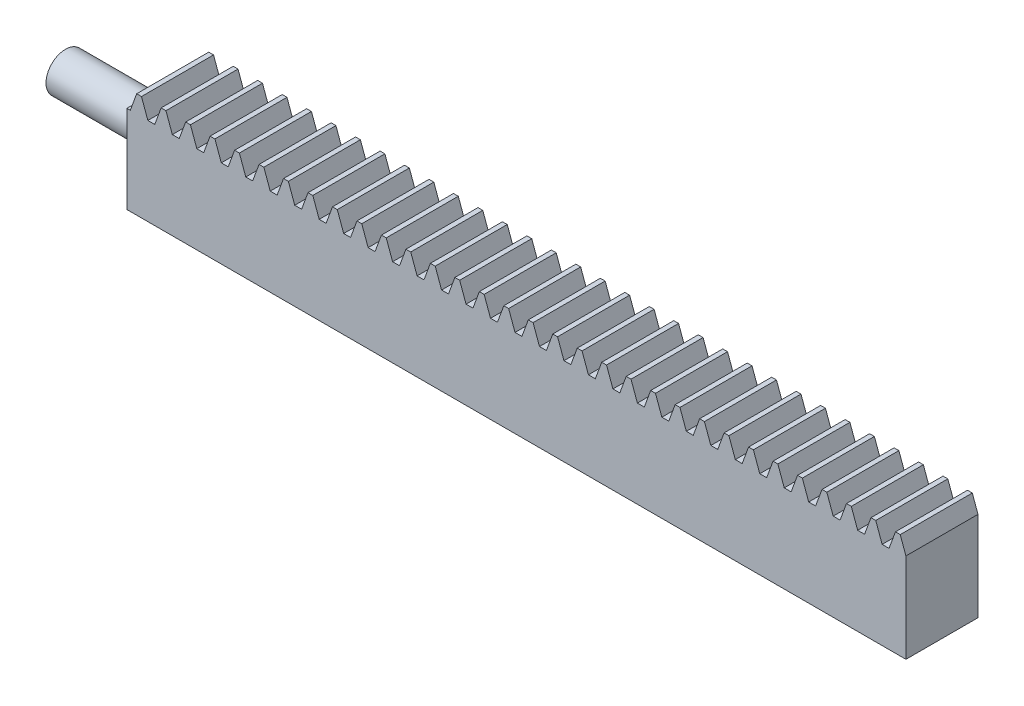
SolidWorks part; units mm, degrees
extrude "Blank" add sketch "BlankSke" against normal blind 7.4
sketch "BlankSke" plane through (0, 0, 0) normal (0, 0, 1) x (1, 0, 0)
  line L1 (0, 0) -> (80, 0)
  line L2 (0, 0) -> (0, 10.8)
  line L3 (0, 10.8) -> (80, 10.8)
  line L4 (80, 0) -> (80, 10.8)
  dimension "Length" = 80
  dimension "Blank_height" = 10.8
ref_plane "Plane1" through (0, 0, 0) normal (0, 0, 1) x (1, 0, 0)
ref_plane "Plane2" through (0, 0, 0) normal (0, 1, 0) x (1, 0, 0)
ref_plane "Plane3" through (0, 0, 0) normal (1, 0, 0) x (0, 0, -1)
other "Configuration Table"
sketch "HoldingSke" plane through (0, 0, 0) normal (0, 1, 0) x (1, 0, 0)
  line L0 (0, 0) -> (0.174, 1.2378)
  line L1 (-15, 0) -> (100, 0) construction
  line L2 (0, 0) -> (-2.1039, 2.3779)
  line L3 (0, 0) -> (-11.863, 4.5341)
  line L4 (0, 0) -> (7.2428, 4.7035)
  line L5 (0, 0) -> (-23.7986, -8.8762)
  line L6 (0, 0) -> (-10.5278, -7.1032)
  line L9 (-71.009, 38.7566) -> (4.1664, 66.1182)
  line L10 (-76.2, 3.1779) -> (-66.2, 3.1779)
  line L11 (0, 0) -> (-7.4, 0)
  line L12 (-76.2, 101.6) -> (-76.17, 101.6)
  line L13 (24.9733, 27.94) -> (52.9518, 28.4284)
  line L14 (24.9733, 27.94) -> (24.9743, 27.94)
  line L15 (24.9733, 27.94) -> (100.4006, 29.5858)
  circle A0 centre (0, 0) radius 19.05
  circle A1 centre (0, 0) radius 5
  circle A2 centre (0, 0) radius 12.7
  dimension "MPH" = 10
  dimension "Diameter" = 38.1
  dimension "Num_teeth" = 33
  dimension "Pitch" = 1.25
  dimension "Show_teeth" = 998
  dimension "Thickness" = 12.7
  dimension "Ap" = 20
  dimension "Pitch_height" = 10
  dimension "Width" = 7.4
  dimension "Backlash" = 0.03
  dimension "Addendum_fac" = 1
  dimension "Dedendum_fac" = 1.25
  dimension "Clearance_fac" = 0.25
  dimension "Dedendum_add" = 0.001
  dimension "Length" = 80
  dimension "Module" = 0.8
sketch "TooCutSkeIll" plane through (0, 0, 0) normal (0, 0, 1) x (1, 0, 0)
  line L0 (-1.0018, 10.7789) -> (-0.4025, 9.1323)
  line L1 (-0.2136, 9) -> (0.2136, 9)
  line L2 (0.4025, 9.1323) -> (1.0018, 10.7789)
  line L3 (80, 10.8) -> (0, 10.8) construction
  line L4 (0, 0) -> (0, 64.897) construction
  line L5 (-13.208, 10) -> (12.954, 10) construction
  line L6 (0, 0) -> (80, 0) construction
  line L7 (0.7183, 10) -> (0.7183, 48.7463) construction
  line L8 (-0.7183, 10) -> (-0.7183, 48.7463) construction
  line L9 (1.0319, 10.8) -> (1.0319, 10.8254)
  line L10 (-1.0319, 10.8) -> (-1.0319, 10.8254)
  line L11 (-1.0319, 10.8254) -> (1.0319, 10.8254)
  arc A0 (0.2136, 9) -> (0.4025, 9.1323) centre (0.2136, 9.201) ccw
  arc A1 (-0.4025, 9.1323) -> (-0.2136, 9) centre (-0.2136, 9.201) ccw
  arc A2 (1.0319, 10.8) -> (1.0018, 10.7789) centre (1.0319, 10.768) ccw
  arc A3 (-1.0018, 10.7789) -> (-1.0319, 10.8) centre (-1.0319, 10.768) ccw
  dimension "Pitch_height" = 10
  dimension "Addendum_plus" = 0.8254
  dimension "Pressure_angle" = 20
  dimension "Gap_width" = 1.4366
  dimension "Dedendum" = 1
extrude "ToothCutIll" [suppressed] cut sketch "TooCutSkeIll" against normal through all
sketch "TooCutSkeSim" plane through (0, 0, 0) normal (0, 0, 1) x (1, 0, 0)
  line L0 (0.3543, 9) -> (-0.3543, 9)
  line L1 (1.0187, 10.8254) -> (0.3543, 9)
  line L2 (0, 17.4625) -> (0, 53.467) construction
  line L3 (1.0187, 10.8254) -> (-1.0187, 10.8254)
  line L6 (-1.0187, 10.8254) -> (-0.3543, 9)
  line L9 (-0.7183, 10) -> (0.7183, 10) construction
  line L10 (0, 0) -> (80, 0) construction
  line L11 (0.7183, 10) -> (0.7183, 53.467) construction
  line L12 (-0.7183, 10) -> (-0.7183, 53.467) construction
  dimension "Pitch_height" = 10
  dimension "Addendum_plus" = 0.8254
  dimension "Pressure_angle" = 20
  dimension "Gap_width" = 1.4366
  dimension "Dedendum" = 1
extrude "ToothCutSim" cut sketch "TooCutSkeSim" against normal through all
pattern_linear "TeethCuts" count 32 spacing 2.5133 along (1, 0, 0) of "ToothCutIll", "ToothCutSim"
sketch "草图1" plane through (0, 0, 0) normal (-1, 0, 0) x (0, 0, 1)
  line L0 (-7.4, 10.8) -> (0, 0) construction
  line L5 (0, 10.8) -> (-7.4, 0) construction
  line L8 (-7.4, 10.8) -> (0, 10.8)
  line L9 (-7.4, 10.8) -> (-7.4, 0)
  line L10 (-7.4, 0) -> (0, 0)
  line L11 (0, 10.8) -> (0, 0)
  circle A0 centre (-3.7, 5.4) radius 2
  dimension "D1" = 4
  dimension "D2" = 10.8
extrude "凸台-拉伸1" add sketch "草图1" along normal blind 10 contours A0
equation "' \"Module@HoldingSke\" = 6.35"
equation "' \"Num_teeth@HoldingSke\" = 12"
equation "' \"Ap@HoldingSke\" =  20"
equation "' \"Ap@HoldingSke\" = 20"
equation "' \"Width@HoldingSke\" = 0.25 * 25.4"
equation "' \"Show_teeth@HoldingSke\" = 500"
equation "' \"Backlash@HoldingSke\" = 0.009 * 25.4"
equation "' \"Addendum_fac@HoldingSke\" = 1.0"
equation "' \"Dedendum_fac@HoldingSke\" = 1.25"
equation "' \"Dedendum_add@HoldingSke\" = 0.00005 * 25.4"
equation "' \"Clearance_fac@HoldingSke\" = 0.25"
equation "' \"Pitch_height@HoldingSke\" = 1 * 25.4"
equation "' \"Length@HoldingSke\" = 4.71 * 25.4"
equation "\"Pitch@HoldingSke\" = 1 / \"Module@HoldingSke\""
equation "\"MPH@HoldingSke\" = \"Dedendum_fac@HoldingSke\" / \"Pitch@HoldingSke\" + 2 * \"Dedendum_add@HoldingSke\" + 0.002 * 25.4"
equation "\"MPH@HoldingSke\" = ((sgn( \"MPH@HoldingSke\" - \"Pitch_height@HoldingSke\")+1)*( \"MPH@HoldingSke\" - \"Pitch_height@HoldingSke\"))/2 + \"Pitch_height@HoldingSke\""
equation "\"Blank_height@BlankSke\" = \"Pitch_height@HoldingSke\" + \"Addendum_fac@HoldingSke\"  / \"Pitch@HoldingSke\" "
equation "\"Length@BlankSke\" =  \"Length@HoldingSke\""
equation "\"Face_width@Blank\" = \"Width@HoldingSke\""
equation "\"Pressure_angle@TooCutSkeIll\" = \"Ap@HoldingSke\""
equation "\"Addendum_plus@TooCutSkeIll\" =  \"Addendum_fac@HoldingSke\"  / \"Pitch@HoldingSke\" + 0.001 *25.4"
equation "\"Dedendum@TooCutSkeIll\" = \"Dedendum_fac@HoldingSke\"  / \"Pitch@HoldingSke\""
equation "\"Pitch_height@TooCutSkeIll\" =  \"MPH@HoldingSke\""
equation "\"Gap_width@TooCutSkeIll\" = 3.14159265 / 2 / \"Pitch@HoldingSke\" + 6 * \"Backlash@HoldingSke\""
equation "\"Pressure_angle@TooCutSkeSim\" = \"Ap@HoldingSke\""
equation "\"Addendum_plus@TooCutSkeSim\" =  \"Addendum_fac@HoldingSke\"  / \"Pitch@HoldingSke\" + 0.001 * 25.4"
equation "\"Dedendum@TooCutSkeSim\" = \"Dedendum_fac@HoldingSke\"  / \"Pitch@HoldingSke\""
equation "\"Pitch_height@TooCutSkeSim\" =  \"MPH@HoldingSke\""
equation "\"Gap_width@TooCutSkeSim\" = 3.14159265 / 2 / \"Pitch@HoldingSke\" + 6 * \"Backlash@HoldingSke\""
equation "\"Root_fillet@TooCutSkeIll\" = \"Clearance_fac@HoldingSke\" / \"Pitch@HoldingSke\" + \"Dedendum_add@HoldingSke\""
equation "\"Break_rad@TooCutSkeIll\" = 0.02 / \"Pitch@HoldingSke\" * 2"
equation "\"Linear_pitch@TeethCuts\" = 3.14159265 / \"Pitch@HoldingSke\""
equation "\"Num_teeth@HoldingSke\" = int( ( \"Length@HoldingSke\" + 0 ) / (3.14159265 / \"Pitch@HoldingSke\")) + 0.9999  + 1"
equation " \"Num_teeth@TeethCuts\" = int( \"Show_teeth@HoldingSke\" ) + 1"
equation " \"Num_teeth@TeethCuts\" = ((sgn( \"Num_teeth@TeethCuts\" - \"Num_teeth@HoldingSke\" )-1)*( \"Num_teeth@TeethCuts\" - \"Num_teeth@HoldingSke\" ))/-2+ \"Num_teeth@HoldingSke\""
equation " \"Num_teeth@TeethCuts\" = ((sgn( \"Num_teeth@TeethCuts\" - 2.0)+1)*( \"Num_teeth@TeethCuts\" - 2.0))/2 +2.0"
